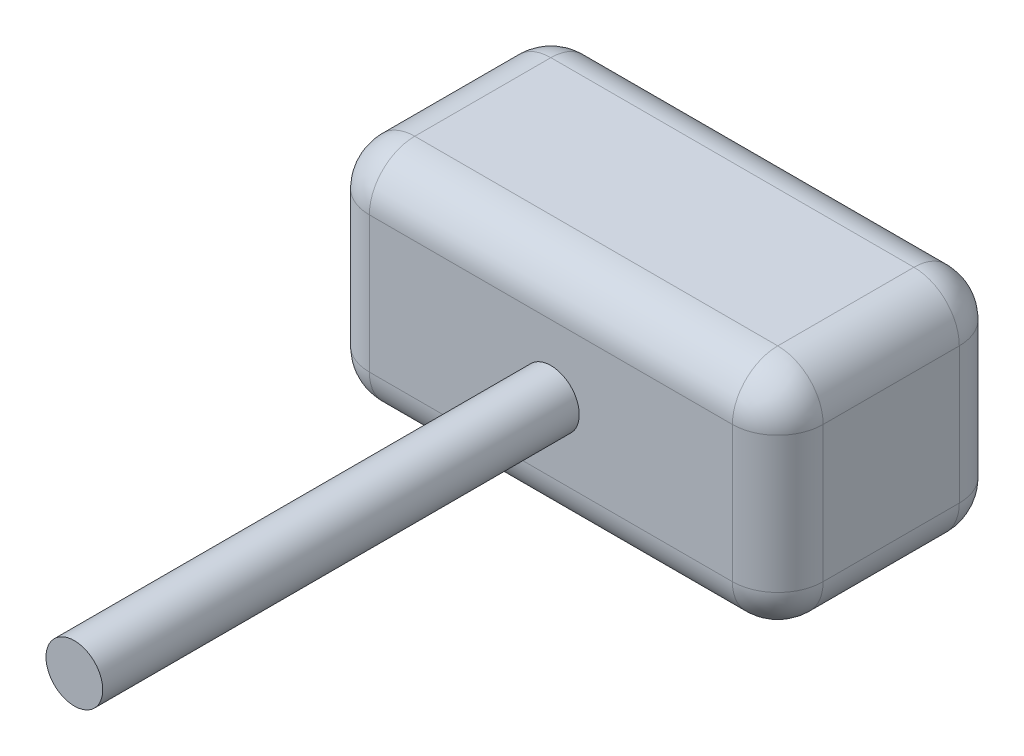
SolidWorks part; units mm, degrees
ref_plane "Front Plane" through (0, 0, 0) normal (0, 0, 1) x (1, 0, 0)
ref_plane "Top Plane" through (0, 0, 0) normal (0, 1, 0) x (1, 0, 0)
ref_plane "Right Plane" through (0, 0, 0) normal (1, 0, 0) x (0, 0, -1)
sketch "Sketch5" plane through (0, 0, 0) normal (0, 0, 1) x (1, 0, 0)
  line L0 (-10, 5) -> (10, 5)
  line L1 (10, 5) -> (10, -5)
  line L2 (10, -5) -> (-10, -5)
  line L3 (-10, -5) -> (-10, 5)
  point P4 (0, 0)
  point P5 (-8.0187, -3.7826)
  point P8 (0, 5)
  point P9 (10, 0)
  dimension "D1" = 20
  dimension "D2" = 10
extrude "Boss-Extrude2" add sketch "Sketch5" along normal mid plane 10
sketch "Sketch6" plane through (0, 0, 0) normal (0, 0, 1) x (1, 0, 0)
  circle A0 centre (0, 0) radius 1.25
  point P2 (0, 0)
  point P3 (0, 0)
  dimension "D1" = 2.5
extrude "Cut-Extrude2" cut sketch "Sketch6" against normal through all both and the other way through all
fillet "Fillet3" radius 2 12 edges at (0, -5, 5) (0, -5, -5) (-10, 0, 5) (-10, -5, 0) (-10, 0, -5) (10, -5, 0) (10, 0, 5) (10, 0, -5) (10, 5, 0) (0, 5, 5) (-10, 5, 0) (0, 5, -5)
sketch "Sketch7" plane through (0, 0, 0) normal (0, 1, 0) x (1, 0, 0)
  line L0 (1.25, 5) -> (-1.25, 5) construction
  line L1 (0, 5) -> (1.25, 5)
  line L2 (0, 5) -> (0, -26)
  line L3 (0, -26) -> (1.25, -26)
  line L4 (1.25, 5) -> (1.25, -26)
  dimension "D1" = 1.25
  dimension "D2" = 31
revolve "Revolve1" add sketch "Sketch7" angle 360 about L2
